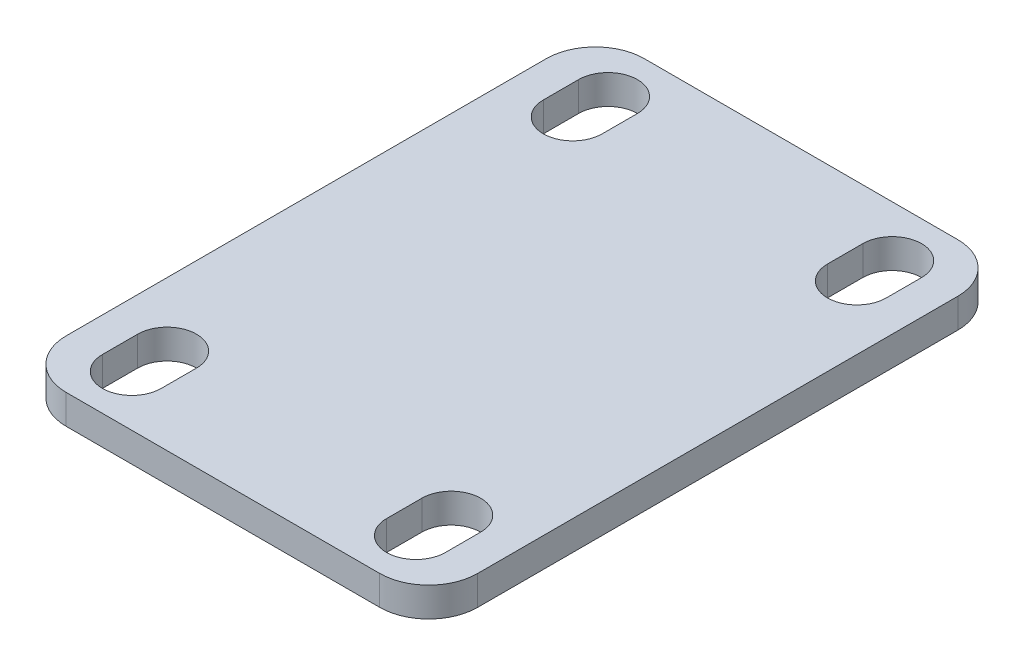
SolidWorks part; units mm, degrees
ref_plane "前视基准面" through (0, 0, 0) normal (0, 0, 1) x (1, 0, 0)
ref_plane "上视基准面" through (0, 0, 0) normal (0, 1, 0) x (1, 0, 0)
ref_plane "右视基准面" through (0, 0, 0) normal (1, 0, 0) x (0, 0, -1)
sketch "草图1" plane through (0, 0, 0) normal (0, 1, 0) x (1, 0, 0)
  line L0 (-14.5, 24.3) -> (-14.5, 20.7) construction
  line L1 (16, -29.5) -> (-16, -29.5)
  line L2 (21, -24.5) -> (21, 24.5)
  line L3 (16, 29.5) -> (-16, 29.5)
  line L4 (-21, -24.5) -> (-21, 24.5)
  line L5 (21, -29.5) -> (-21, 29.5) construction
  line L6 (21, 29.5) -> (-21, -29.5) construction
  line L7 (-11.5, 24.3) -> (-11.5, 20.7)
  line L8 (-17.5, 24.3) -> (-17.5, 20.7)
  line L9 (0, 0) -> (-17.5, 0) construction
  line L10 (0, 0) -> (0, 21.0324) construction
  line L11 (14.5, 24.3) -> (14.5, 20.7) construction
  line L12 (11.5, 24.3) -> (11.5, 20.7)
  line L13 (17.5, 24.3) -> (17.5, 20.7)
  line L14 (-14.5, -24.3) -> (-14.5, -20.7) construction
  line L15 (-11.5, -24.3) -> (-11.5, -20.7)
  line L16 (-17.5, -24.3) -> (-17.5, -20.7)
  line L17 (14.5, -24.3) -> (14.5, -20.7) construction
  line L18 (11.5, -24.3) -> (11.5, -20.7)
  line L19 (17.5, -24.3) -> (17.5, -20.7)
  arc A0 (-11.5, 24.3) -> (-17.5, 24.3) centre (-14.5, 24.3) ccw
  arc A1 (-17.5, 20.7) -> (-11.5, 20.7) centre (-14.5, 20.7) ccw
  arc A2 (11.5, 24.3) -> (17.5, 24.3) centre (14.5, 24.3) cw
  arc A3 (17.5, 20.7) -> (11.5, 20.7) centre (14.5, 20.7) cw
  arc A4 (-11.5, -24.3) -> (-17.5, -24.3) centre (-14.5, -24.3) cw
  arc A5 (-17.5, -20.7) -> (-11.5, -20.7) centre (-14.5, -20.7) cw
  arc A6 (11.5, -24.3) -> (17.5, -24.3) centre (14.5, -24.3) ccw
  arc A7 (17.5, -20.7) -> (11.5, -20.7) centre (14.5, -20.7) ccw
  arc A8 (16, -29.5) -> (21, -24.5) centre (16, -24.5) ccw
  arc A9 (-16, -29.5) -> (-21, -24.5) centre (-16, -24.5) cw
  arc A10 (21, 24.5) -> (16, 29.5) centre (16, 24.5) ccw
  arc A11 (-16, 29.5) -> (-21, 24.5) centre (-16, 24.5) ccw
  point P0 (0, 0)
  point P8 (-14.5, 22.5)
  point P13 (-14.5, 27.3)
  point P14 (-14.5, 17.7)
  point P20 (14.5, 22.5)
  point P27 (-14.5, -22.5)
  point P34 (14.5, -22.5)
  dimension "D3" = 6
  dimension "D7" = 5
  dimension "D1" = 42
  dimension "D2" = 59
  dimension "D4" = 9.6
  dimension "D5" = 45
  dimension "D6" = 29
extrude "凸台-拉伸1" add sketch "草图1" along normal blind 3
sketch "草图2" plane through (0, 0, 0) normal (0, -1, 0) x (1, 0, 0)
  circle A0 centre (0, 0) radius 17.5
  dimension "D1" = 35
extrude "凸台-拉伸2" add sketch "草图2" along normal blind 3
